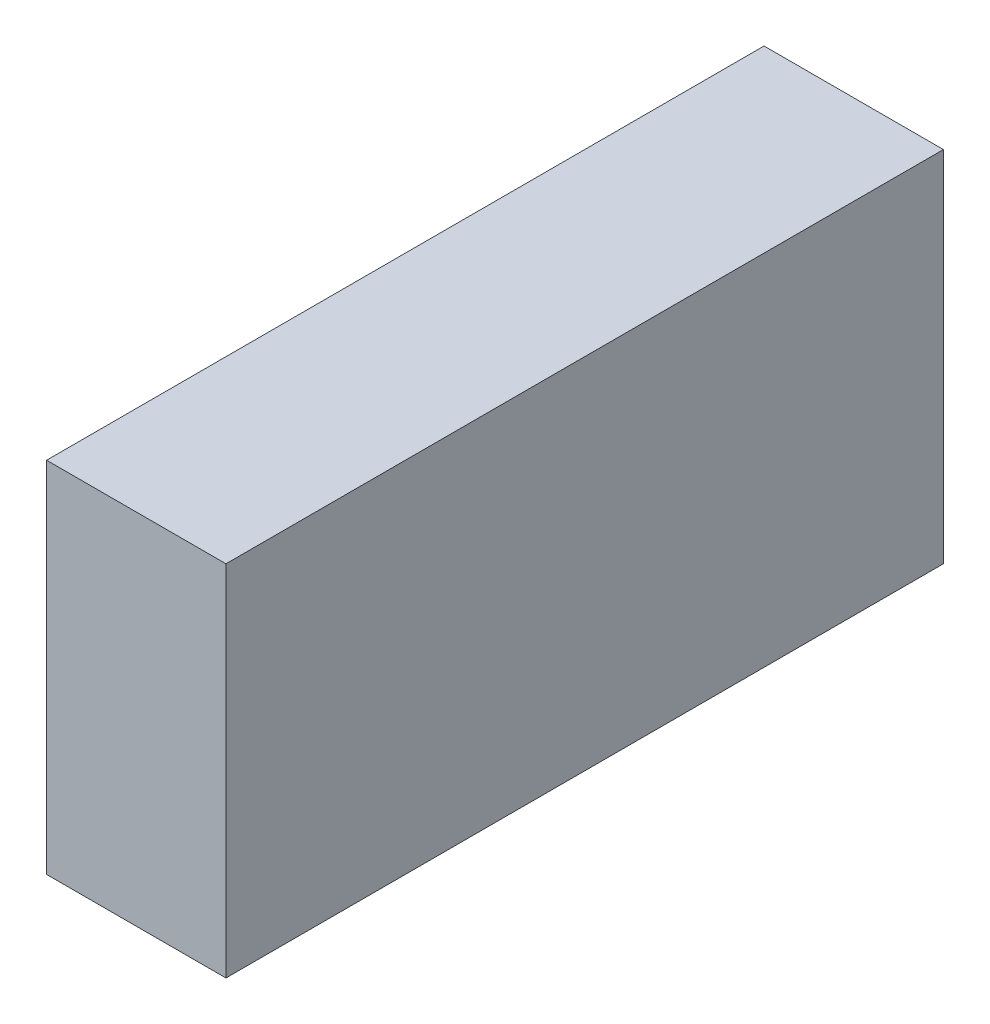
SolidWorks part; units mm, degrees
ref_plane "前基準面" through (0, 0, 0) normal (0, 0, 1) x (1, 0, 0)
ref_plane "上基準面" through (0, 0, 0) normal (0, 1, 0) x (1, 0, 0)
ref_plane "右基準面" through (0, 0, 0) normal (1, 0, 0) x (0, 0, -1)
sketch "草圖1" plane through (0, 0, 0) normal (0, 0, 1) x (1, 0, 0)
  line L1 (-2.7035, 1.3154) -> (17.2965, 1.3154)
  line L2 (-2.7035, 1.3154) -> (-2.7035, -38.6846)
  line L3 (-2.7035, -38.6846) -> (17.2965, -38.6846)
  line L4 (17.2965, 1.3154) -> (17.2965, -38.6846)
  dimension "D1" = 20
  dimension "D2" = 40
extrude "填料-伸長2" add sketch "草圖1" along normal blind 80
